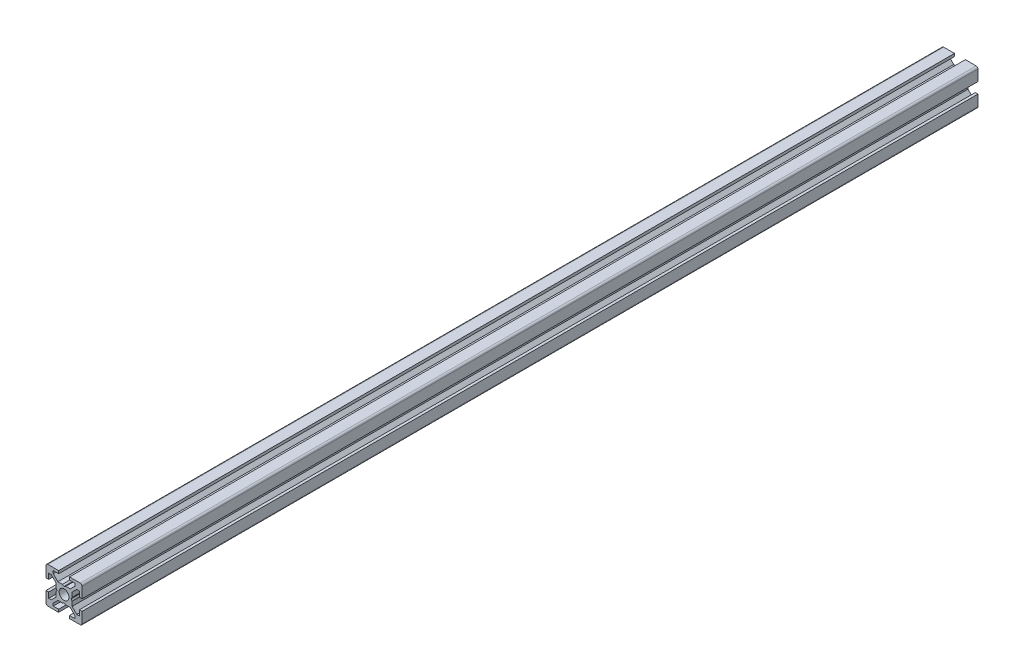
SolidWorks part; units mm, degrees
ref_plane "Front Plane" through (0, 0, 0) normal (0, 0, 1) x (1, 0, 0)
ref_plane "Top Plane" through (0, 0, 0) normal (0, 1, 0) x (1, 0, 0)
ref_plane "Right Plane" through (0, 0, 0) normal (1, 0, 0) x (0, 0, -1)
sketch "Sketch1" plane through (0, 0, 0) normal (0, 0, 1) x (1, 0, 0)
  line L0 (-707.1068, -707.1068) -> (34648.2323, 34648.2323) construction
  line L1 (-3.0018, 10) -> (-10, 10)
  line L2 (0.9376, 4.4579) -> (-0.0011, 3.9339)
  line L3 (3.4252, 4.4579) -> (0.9376, 4.4579)
  line L4 (6.0128, 7.0454) -> (3.4252, 4.4579)
  line L5 (0, -1000) -> (0, 49000) construction
  line L6 (-1000, 0) -> (49000, 0) construction
  line L7 (6.0128, 8.5) -> (6.0128, 7.0454)
  line L8 (3.0018, 8.5) -> (6.0128, 8.5)
  line L9 (3.0018, 10) -> (10, 10)
  line L10 (3.0018, 8.5) -> (3.0018, 10)
  line L11 (-707.1068, 707.1068) -> (34648.2323, -34648.2323) construction
  line L12 (-7.0458, 6.0144) -> (-4.4582, 3.4268)
  line L13 (-8.5008, 6.0144) -> (-7.0458, 6.0144)
  line L14 (-8.5008, 3.0018) -> (-8.5008, 6.0144)
  line L15 (0, -0.0423) -> (0.0002, 2.0704) construction
  line L16 (-10, 3.0018) -> (-10, 10)
  line L17 (-8.5008, 3.0018) -> (-10, 3.0018)
  line L18 (8.5, 3.0018) -> (10, 3.0018)
  line L19 (10, 3.0018) -> (10, 10)
  line L20 (8.5, 3.0018) -> (8.5, 6.0143)
  line L21 (8.5, 6.0143) -> (7.0454, 6.0143)
  line L22 (7.0454, 6.0143) -> (4.4583, 3.4262)
  line L23 (-3.0018, 8.5) -> (-3.0018, 10)
  line L24 (-3.0018, 8.5) -> (-6.0148, 8.5)
  line L25 (-6.0148, 8.5) -> (-6.0148, 7.0458)
  line L26 (-6.0148, 7.0458) -> (-3.4272, 4.4582)
  line L27 (-3.4272, 4.4582) -> (-0.9396, 4.4582)
  line L28 (-0.9396, 4.4582) -> (-0.0011, 3.9339)
  line L29 (-4.4582, 3.4268) -> (-4.4582, 0.9396)
  line L30 (-4.4582, 0.9396) -> (-3.9347, 0)
  line L31 (4.4575, 0.9396) -> (3.9347, 0)
  line L32 (4.4583, 3.4262) -> (4.4575, 0.9396)
  line L37 (-0.9396, -4.4582) -> (-0.0011, -3.9339)
  line L45 (-3.4272, -4.4582) -> (-0.9396, -4.4582)
  line L46 (-6.0148, -7.0458) -> (-3.4272, -4.4582)
  line L47 (-6.0148, -8.5) -> (-6.0148, -7.0458)
  line L48 (-3.0018, -8.5) -> (-6.0148, -8.5)
  line L49 (-3.0018, -10) -> (-10, -10)
  line L50 (-3.0018, -8.5) -> (-3.0018, -10)
  line L51 (4.4588, -0.9386) -> (3.9347, 0)
  line L52 (4.4583, -3.4262) -> (4.4588, -0.9386)
  line L53 (7.0454, -6.0143) -> (4.4583, -3.4262)
  line L54 (8.5, -6.0143) -> (7.0454, -6.0143)
  line L55 (8.5, -3.0018) -> (8.5, -6.0143)
  line L56 (10, -3.0018) -> (10, -10)
  line L57 (8.5, -3.0018) -> (10, -3.0018)
  line L58 (-8.5008, -3.0018) -> (-10, -3.0018)
  line L59 (-10, -3.0018) -> (-10, -10)
  line L60 (-8.5008, -3.0018) -> (-8.5008, -6.0144)
  line L61 (-8.5008, -6.0144) -> (-7.0458, -6.0144)
  line L62 (-7.0458, -6.0144) -> (-4.4582, -3.4268)
  line L63 (-4.4582, -3.4268) -> (-4.4575, -0.9396)
  line L64 (-4.4575, -0.9396) -> (-3.9347, 0)
  line L65 (3.0018, -8.5) -> (3.0018, -10)
  line L66 (3.0018, -10) -> (10, -10)
  line L67 (3.0018, -8.5) -> (6.0128, -8.5)
  line L68 (6.0128, -8.5) -> (6.0128, -7.0454)
  line L69 (6.0128, -7.0454) -> (3.4252, -4.4579)
  line L70 (3.4252, -4.4579) -> (0.9376, -4.4579)
  line L71 (0.9376, -4.4579) -> (-0.0011, -3.9339)
  circle A0 centre (0, 0) radius 2.75
extrude "Boss-Extrude1" add sketch "Sketch1" along normal blind 496
fillet "Fillet2" radius 1 1 edges at (-10, -10, 248)
fillet "Fillet3" radius 1 1 edges at (10, -10, 248)
fillet "Fillet4" radius 1 1 edges at (-10, 10, 248)
fillet "Fillet5" radius 1 1 edges at (10, 10, 248)
